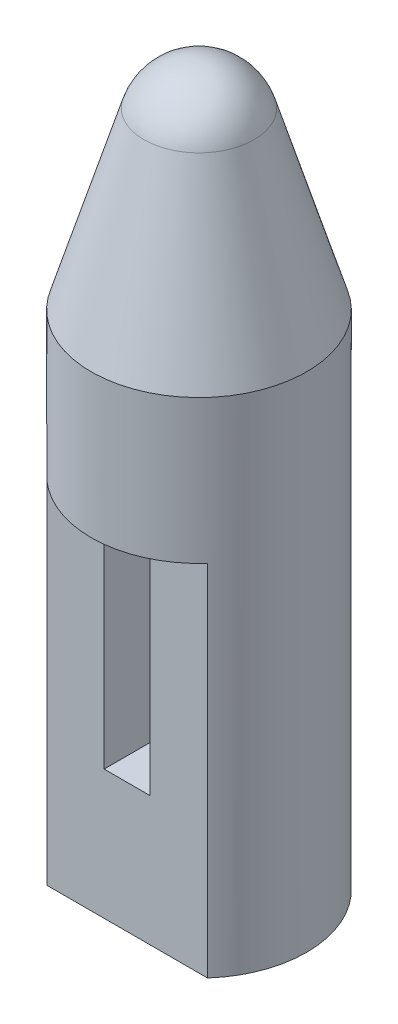
SolidWorks part; units mm, degrees
ref_plane "前视基准面" through (0, 0, 0) normal (0, 0, 1) x (1, 0, 0)
ref_plane "上视基准面" through (0, 0, 0) normal (0, 1, 0) x (1, 0, 0)
ref_plane "右视基准面" through (0, 0, 0) normal (1, 0, 0) x (0, 0, -1)
sketch "草图1" plane through (0, 0, 0) normal (0, 0, 1) x (1, 0, 0)
  line L0 (-16.3403, 47.5405) -> (-16.3403, -2.4595)
  line L1 (-16.3403, -2.4595) -> (-8.8403, -2.4595)
  line L2 (-8.8403, -2.4595) -> (-8.8403, 32.5405)
  line L3 (-8.8403, 32.5405) -> (-12.511, 44.6968)
  arc A0 (-12.511, 44.6968) -> (-16.3403, 47.5405) centre (-16.3403, 43.5405) ccw
  dimension "D1" = 8
  dimension "D2" = 50
  dimension "D3" = 7.5
  dimension "D4" = 35
revolve "旋转1" add sketch "草图1" angle 360 about L0
sketch "草图2" plane through (0, -2.4595, 0) normal (0, -1, 0) x (1, 0, 0)
  line L1 (-21.9304, 5) -> (-10.7501, 5)
  line L3 (-21.9304, -5) -> (-10.7501, -5)
  arc A0 (-21.9304, -5) -> (-10.7501, -5) centre (-16.3403, 0) ccw
  arc A1 (-10.7501, 5) -> (-21.9304, 5) centre (-16.3403, 0) ccw
  dimension "D1" = 5
extrude "切除-拉伸1" cut sketch "草图2" against normal blind 25
sketch "草图3" plane through (0, 0, 5) normal (0, 0, 1) x (1, 0, 0)
  line L1 (-14.7403, 22.5405) -> (-17.9403, 22.5405)
  line L3 (-14.7403, 6.5405) -> (-17.9403, 6.5405)
  line L4 (-17.9403, 22.5405) -> (-17.9403, 6.5405)
  line L5 (-14.7403, 22.5405) -> (-14.7403, 6.5405)
  dimension "D2" = 16
extrude "切除-拉伸2" cut sketch "草图3" against normal blind 4
sketch "草图4" plane through (0, 0, 1) normal (0, 0, 1) x (1, 0, 0)
  line L0 (-17.9403, 6.5405) -> (-14.7403, 6.5405) construction
  circle A0 centre (-16.3403, 13.5405) radius 1.6
  dimension "D1" = 7
extrude "切除-拉伸3" cut sketch "草图4" against normal blind 10
